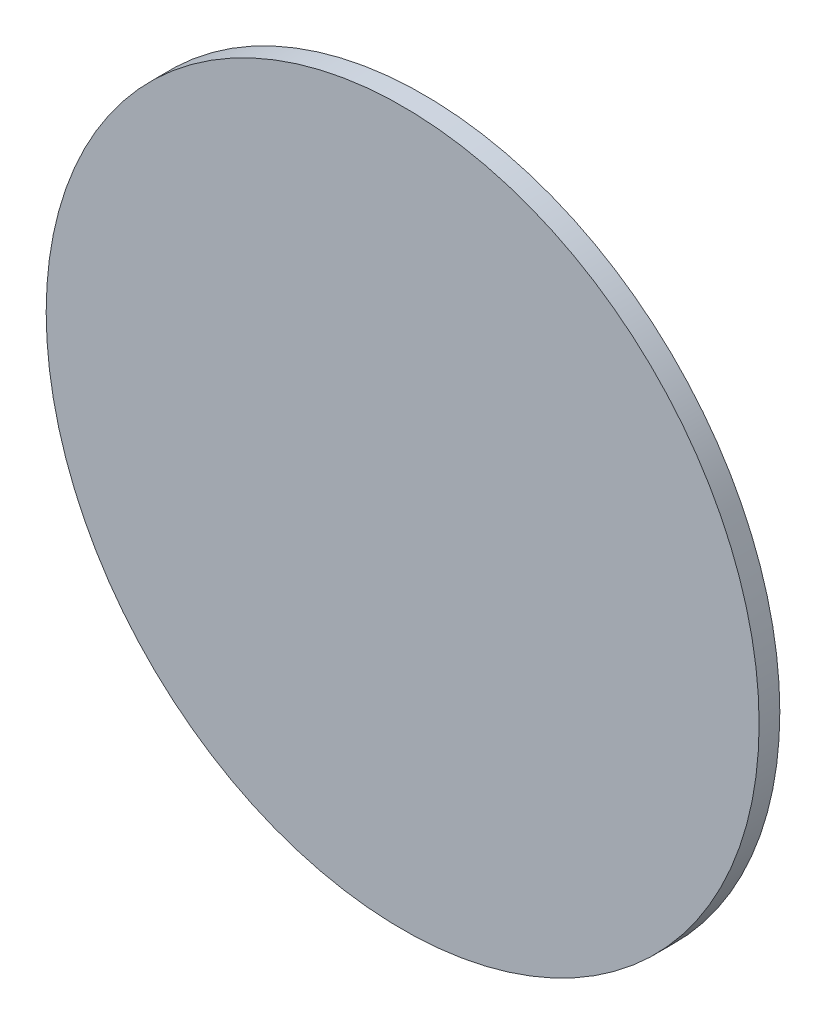
SolidWorks part; units mm, degrees
material "A-Glass Fiber"
ref_plane "Front Plane" through (0, 0, 0) normal (0, 0, 1) x (1, 0, 0)
ref_plane "Top Plane" through (0, 0, 0) normal (0, 1, 0) x (1, 0, 0)
ref_plane "Right Plane" through (0, 0, 0) normal (1, 0, 0) x (0, 0, -1)
sketch "Sketch1" plane through (0, 0, 0) normal (0, 0, 1) x (1, 0, 0)
  circle A0 centre (0, 0) radius 172.204
extrude "Boss-Extrude1" add sketch "Sketch1" along normal blind 10
